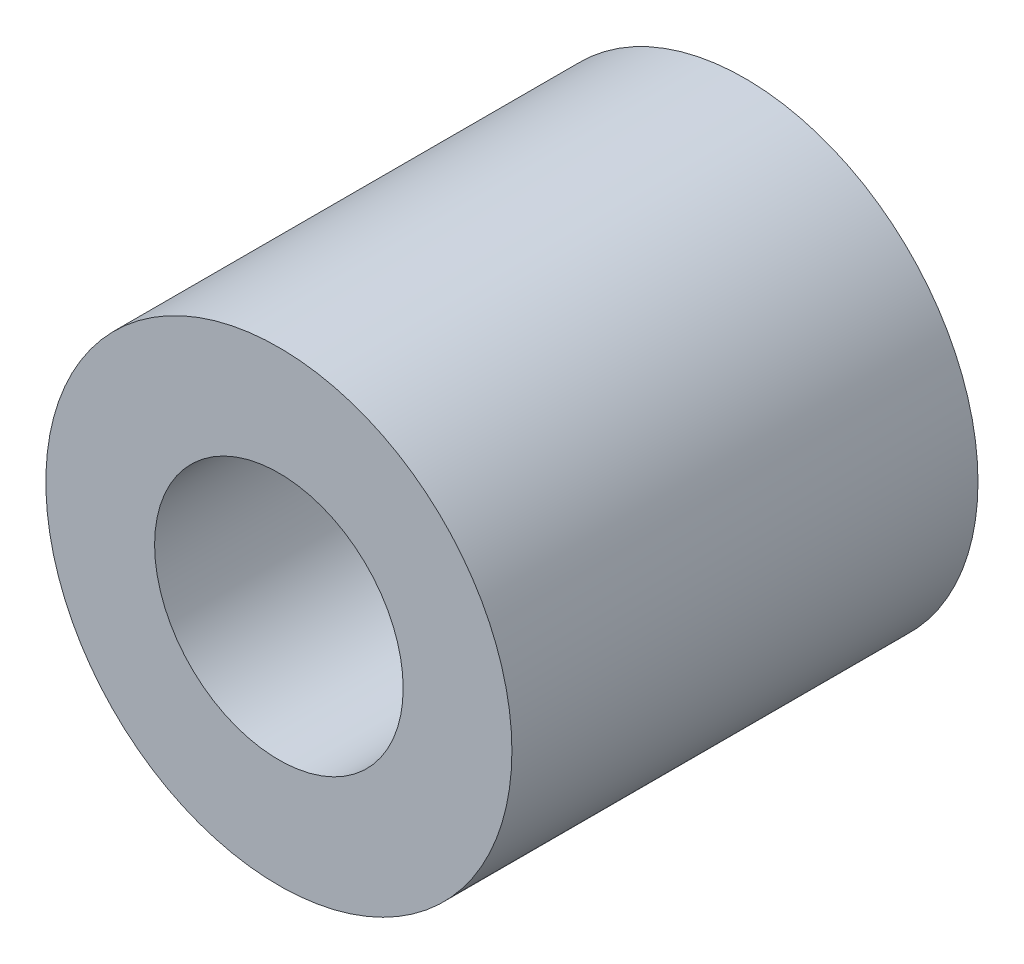
SolidWorks part; units mm, degrees
material "6063-T5"
ref_plane "正面" through (0, 0, 0) normal (0, 0, 1) x (1, 0, 0)
ref_plane "平面" through (0, 0, 0) normal (0, 1, 0) x (1, 0, 0)
ref_plane "右側面" through (0, 0, 0) normal (1, 0, 0) x (0, 0, -1)
sketch "ｽｹｯﾁ1" plane through (0, 0, 0) normal (0, 0, 1) x (1, 0, 0)
  circle A0 centre (0, 0) radius 3
  circle A1 centre (0, 0) radius 1.6
  dimension "D1" = 3.2
  dimension "D2" = 6
extrude "ﾎﾞｽ - 押し出し1" add sketch "ｽｹｯﾁ1" along normal blind 6
